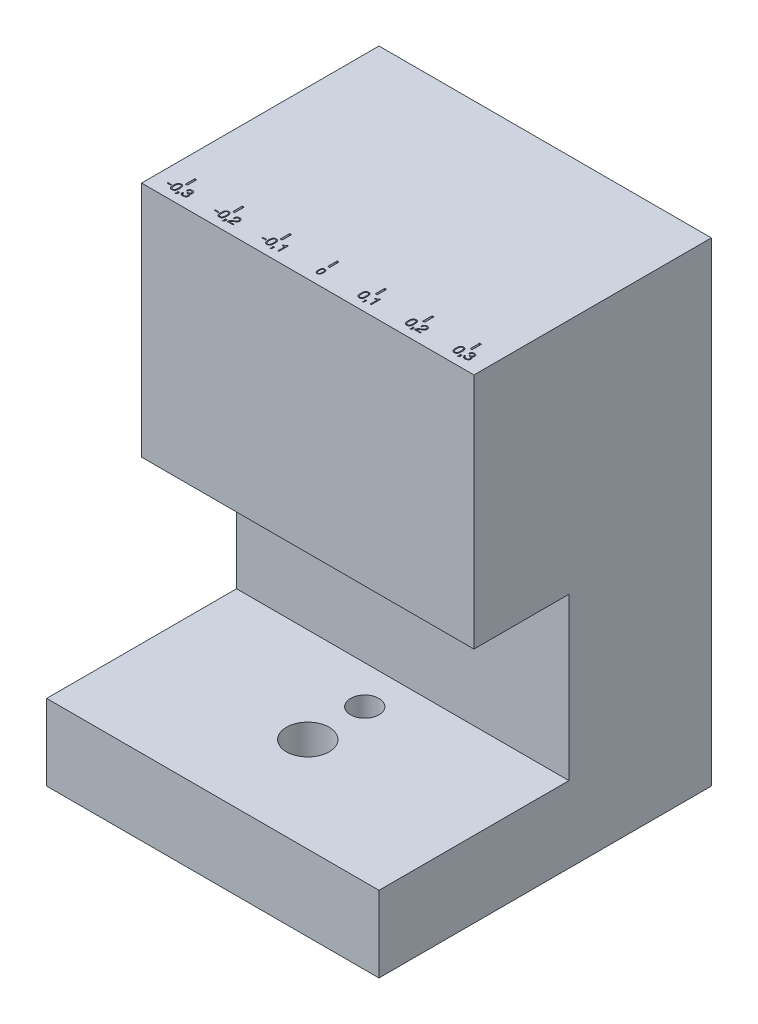
SolidWorks part; units mm, degrees
ref_plane "Front Plane" through (0, 0, 0) normal (0, 0, 1) x (1, 0, 0)
ref_plane "Top Plane" through (0, 0, 0) normal (0, 1, 0) x (1, 0, 0)
ref_plane "Right Plane" through (0, 0, 0) normal (1, 0, 0) x (0, 0, -1)
sketch "Sketch1" plane through (0, 0, 0) normal (0, 1, 0) x (1, 0, 0)
  line L1 (-17.5, -17.5) -> (17.5, -17.5)
  line L2 (-17.5, -17.5) -> (-17.5, 17.5)
  line L3 (-17.5, 17.5) -> (17.5, 17.5)
  line L4 (17.5, -17.5) -> (17.5, 17.5)
  line L5 (-17.5, -17.5) -> (17.5, 17.5) construction
  line L6 (-17.5, 17.5) -> (17.5, -17.5) construction
  point P0 (0, 0)
extrude "Boss-Extrude1" add sketch "Sketch1" along normal blind 50
sketch "Sketch2" plane through (0, 0, 17.5) normal (0, 0, 1) x (1, 0, 0)
  line L0 (17.5, 50) -> (17.5, 0) construction
  line L1 (-17.5, 50) -> (17.5, 50)
  line L2 (-17.5, 50) -> (-17.5, 8)
  line L3 (-17.5, 8) -> (17.5, 8)
  line L4 (17.5, 50) -> (17.5, 8)
extrude "Cut-Extrude1" cut sketch "Sketch2" against normal blind 10
sketch "Sketch3" plane through (0, 0, 7.5) normal (0, 0, 1) x (1, 0, 0)
  line L0 (17.5, 8) -> (17.5, 50) construction
  line L1 (-17.5, 8) -> (17.5, 8)
  line L2 (-17.5, 8) -> (-17.5, 25)
  line L3 (-17.5, 25) -> (17.5, 25)
  line L4 (17.5, 8) -> (17.5, 25)
extrude "Cut-Extrude2" cut sketch "Sketch3" against normal blind 10
sketch "Sketch4" plane through (0, 0, 0) normal (0, -1, 0) x (1, 0, 0)
  line L0 (0, 17.5) -> (0, -19.0803) construction
  line L1 (-17.5, 17.5) -> (17.5, 17.5) construction
  line L2 (-25.823, 0) -> (33.1874, 0) construction
sketch "Sketch5" plane through (0, 0, 0) normal (0, -1, 0) x (1, 0, 0)
  line L0 (0, 17.5) -> (0, -19.0803) construction
  line L2 (-17.5, 17.5) -> (17.5, 17.5) construction
  circle A0 centre (0, 1.5) radius 1.5
  dimension "D1" = 16
  dimension "D2" = 3
extrude "Cut-Extrude3" cut sketch "Sketch5" against normal up to next
sketch "Sketch6" plane through (0, 0, 0) normal (0, -1, 0) x (1, 0, 0)
  circle A0 centre (0, 7.5) radius 2.25
  circle A1 centre (0, 1.5) radius 1.5 construction
  dimension "D2" = 4.5
  dimension "D1" = 6
extrude "Cut-Extrude4" cut sketch "Sketch6" against normal up to next
sketch "Sketch7" plane through (0, 50, 0) normal (0, 1, 0) x (1, 0, 0)
  line L0 (-17, -6.5) -> (-13, -6.5) construction
  line L1 (17.5, -7.5) -> (-17.5, -7.5) construction
  line L2 (0, -17.5) -> (0, 19.0803) construction
  line L4 (-15.1, -4.3) -> (-14.9, -4.3)
  line L5 (-15.1, -4.3) -> (-15.1, -5.3)
  line L6 (-15.1, -5.3) -> (-14.9, -5.3)
  line L7 (-14.9, -4.3) -> (-14.9, -5.3)
  text T0 "-0,3" font "TUM Neue Helvetica 55 Regular" height 1
  point P2 (-15, -5.3)
  point P3 (-15, -6.5)
  point P4 (0, 0)
  dimension "D1" = 1
  dimension "D2" = 0.2
  dimension "D3" = 1
  dimension "D4" = 1.2
  dimension "D5" = 15
sketch "Sketch10" plane through (0, 50, 0) normal (0, 1, 0) x (1, 0, 0)
  line L0 (-12, -6.5) -> (-8, -6.5) construction
  line L1 (17.5, -7.5) -> (-17.5, -7.5) construction
  line L2 (0, -17.5) -> (0, 19.0803) construction
  line L4 (-10.1, -4.3) -> (-9.9, -4.3)
  line L5 (-10.1, -4.3) -> (-10.1, -5.3)
  line L6 (-10.1, -5.3) -> (-9.9, -5.3)
  line L7 (-9.9, -4.3) -> (-9.9, -5.3)
  text T0 "-0,2" font "TUM Neue Helvetica 55 Regular" height 1
  point P2 (-10, -5.3)
  point P3 (-10, -6.5)
  dimension "D1" = 0.2
  dimension "D2" = 1
  dimension "D3" = 1.2
  dimension "D4" = 1
  dimension "D5" = 10
sketch "Sketch12" plane through (0, 50, 0) normal (0, 1, 0) x (1, 0, 0)
  line L0 (-7, -6.5) -> (-3, -6.5) construction
  line L1 (17.5, -7.5) -> (-17.5, -7.5) construction
  line L2 (0, -17.5) -> (0, 19.0803) construction
  line L4 (-5.1, -4.3) -> (-4.9, -4.3)
  line L5 (-5.1, -4.3) -> (-5.1, -5.3)
  line L6 (-5.1, -5.3) -> (-4.9, -5.3)
  line L7 (-4.9, -4.3) -> (-4.9, -5.3)
  text T0 "-0,1" font "TUM Neue Helvetica 55 Regular" height 1
  point P2 (-5, -5.3)
  point P3 (-5, -6.5)
  dimension "D1" = 1
  dimension "D2" = 1.2
  dimension "D3" = 5
  dimension "D4" = 0.2
  dimension "D5" = 1
sketch "Sketch13" plane through (0, 50, 0) normal (0, 1, 0) x (1, 0, 0)
  line L0 (-2, -6.5) -> (2, -6.5) construction
  line L1 (0, -17.5) -> (0, 19.0803) construction
  line L2 (17.5, -7.5) -> (-17.5, -7.5) construction
  line L4 (-0.1, -4.3) -> (0.1, -4.3)
  line L5 (-0.1, -4.3) -> (-0.1, -5.3)
  line L6 (-0.1, -5.3) -> (0.1, -5.3)
  line L7 (0.1, -4.3) -> (0.1, -5.3)
  text T0 "0" font "TUM Neue Helvetica 55 Regular" height 0.8
  point P2 (0, -5.3)
  point P3 (0, -6.5)
  dimension "D1" = 1
  dimension "D2" = 1.2
sketch "Sketch14" plane through (0, 50, 0) normal (0, 1, 0) x (1, 0, 0)
  line L0 (3, -6.5) -> (7, -6.5) construction
  line L1 (17.5, -7.5) -> (-17.5, -7.5) construction
  line L2 (0, -17.5) -> (0, 19.0803) construction
  line L4 (4.9, -4.3) -> (5.1, -4.3)
  line L5 (4.9, -4.3) -> (4.9, -5.3)
  line L6 (4.9, -5.3) -> (5.1, -5.3)
  line L7 (5.1, -4.3) -> (5.1, -5.3)
  text T0 "0,1" font "TUM Neue Helvetica 55 Regular" height 1
  point P2 (5, -5.3)
  point P3 (5, -6.5)
  dimension "D1" = 0.2
  dimension "D2" = 1
  dimension "D3" = 1.2
  dimension "D4" = 1
  dimension "D5" = 5
sketch "Sketch15" plane through (0, 50, 0) normal (0, 1, 0) x (1, 0, 0)
  line L0 (8, -6.5) -> (12, -6.5) construction
  line L1 (17.5, -7.5) -> (-17.5, -7.5) construction
  line L2 (0, -17.5) -> (0, 19.0803) construction
  line L4 (9.9, -4.3) -> (10.1, -4.3)
  line L5 (9.9, -4.3) -> (9.9, -5.3)
  line L6 (9.9, -5.3) -> (10.1, -5.3)
  line L7 (10.1, -4.3) -> (10.1, -5.3)
  text T0 "0,2" font "TUM Neue Helvetica 55 Regular" height 1
  point P2 (10, -5.3)
  point P3 (10, -6.5)
  dimension "D1" = 1
  dimension "D2" = 10
  dimension "D3" = 1.2
  dimension "D4" = 0.2
  dimension "D5" = 1
sketch "Sketch16" plane through (0, 50, 0) normal (0, 1, 0) x (1, 0, 0)
  line L0 (13, -6.5) -> (17, -6.5) construction
  line L1 (17.5, -7.5) -> (-17.5, -7.5) construction
  line L2 (0, -17.5) -> (0, 19.0803) construction
  line L4 (14.9, -4.3) -> (15.1, -4.3)
  line L5 (14.9, -4.3) -> (14.9, -5.3)
  line L6 (14.9, -5.3) -> (15.1, -5.3)
  line L7 (15.1, -4.3) -> (15.1, -5.3)
  text T0 "0,3" font "TUM Neue Helvetica 55 Regular" height 1
  point P2 (15, -5.3)
  point P3 (15, -6.5)
  dimension "D1" = 4
  dimension "D2" = 0.2
  dimension "D3" = 1
  dimension "D4" = 1.2
  dimension "D5" = 1
  dimension "D6" = 15
extrude "Cut-Extrude5" cut sketch "Sketch13" against normal blind 1
extrude "Cut-Extrude6" cut sketch "Sketch7" against normal blind 1
extrude "Cut-Extrude7" cut sketch "Sketch10" against normal blind 1
extrude "Cut-Extrude8" cut sketch "Sketch12" against normal blind 1
extrude "Cut-Extrude9" cut sketch "Sketch14" against normal blind 1
extrude "Cut-Extrude10" cut sketch "Sketch15" against normal blind 1
extrude "Cut-Extrude11" cut sketch "Sketch16" against normal blind 1
